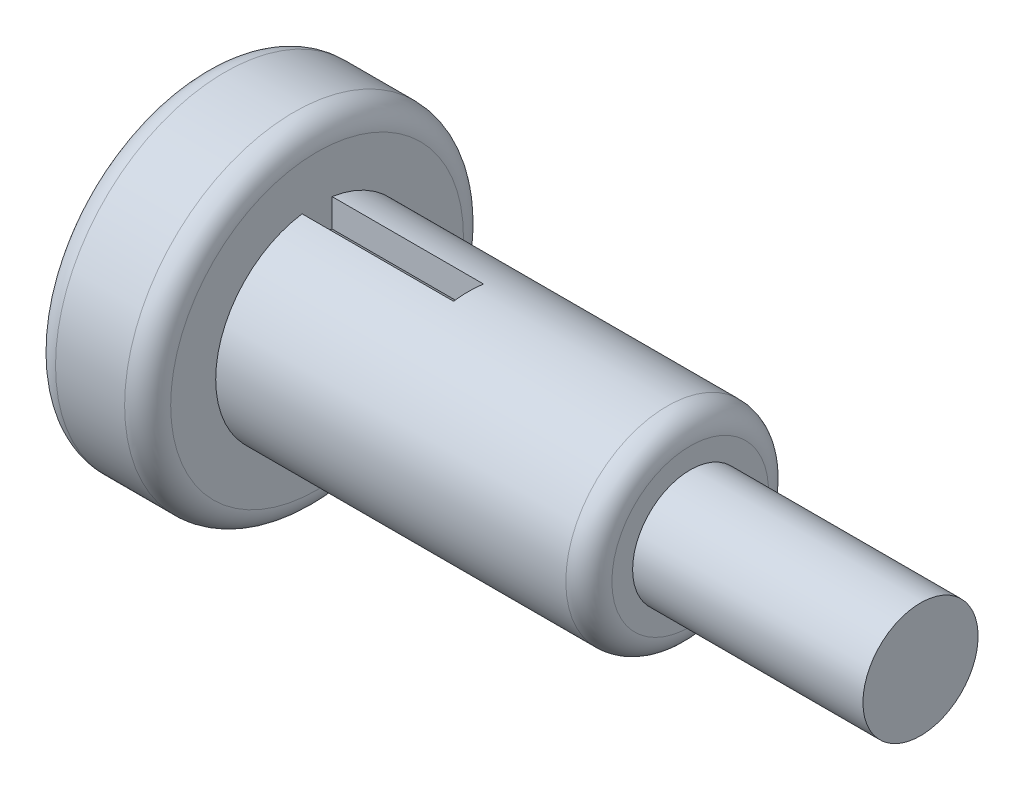
SolidWorks part; units mm, degrees
ref_plane "Front Plane" through (0, 0, 0) normal (0, 0, 1) x (1, 0, 0)
ref_plane "Top Plane" through (0, 0, 0) normal (0, 1, 0) x (1, 0, 0)
ref_plane "Right Plane" through (0, 0, 0) normal (1, 0, 0) x (0, 0, -1)
sketch "Sketch1" plane through (0, 0, 0) normal (0, 1, 0) x (1, 0, 0)
  line L0 (-25.6769, 0) -> (44.3231, 0)
  line L1 (44.3231, 0) -> (44.3231, 12.5)
  line L2 (44.3231, 12.5) -> (-5.6769, 12.5)
  line L3 (-5.6769, 12.5) -> (-5.6769, 17)
  line L4 (-10.6769, 22) -> (-86.6769, 22)
  line L5 (-86.6769, 22) -> (-86.6769, 31.7744)
  line L6 (-91.6769, 36.7744) -> (-106.6769, 36.7744)
  line L7 (-111.6769, 31.7744) -> (-111.6769, 21)
  line L8 (-106.6769, 16) -> (-25.6769, 16)
  line L9 (-25.6769, 16) -> (-25.6769, 0)
  arc A0 (-5.6769, 17) -> (-10.6769, 22) centre (-10.6769, 17) ccw
  arc A1 (-86.6769, 31.7744) -> (-91.6769, 36.7744) centre (-91.6769, 31.7744) ccw
  arc A2 (-106.6769, 16) -> (-111.6769, 21) centre (-106.6769, 21) cw
  arc A3 (-111.6769, 31.7744) -> (-106.6769, 36.7744) centre (-106.6769, 31.7744) cw
  point P14 (-5.6769, 22)
  point P17 (-86.6769, 36.7744)
  point P22 (-111.6769, 36.7744)
  dimension "D9" = 5
  dimension "D2" = 12.5
  dimension "D4" = 50
  dimension "D5" = 20
  dimension "D6" = 25
  dimension "D7" = 106
  dimension "D8" = 16
revolve "Revolve3" add sketch "Sketch1" angle 360 about L0
sketch "Sketch3" plane through (0, 0, 0) normal (0, 0, 1) x (1, 0, 0)
  line L0 (-86.6769, 0) -> (-86.6769, 50)
  line L1 (-86.6769, -22) -> (-86.6769, 22) construction
  line L2 (-86.6769, 0) -> (-86.6769, -56.4071)
  line L4 (-59.6769, -56.4071) -> (-51.6769, 50)
  line L6 (-86.6769, 50) -> (-51.6769, 50)
  line L7 (-86.6769, -56.4071) -> (-59.6769, -56.4071)
  dimension "D1" = 35
  dimension "D2" = 27
  dimension "D3" = 50
  dimension "D4" = 56.4071
extrude "Cut-Extrude1" cut sketch "Sketch3" against normal mid plane 6.5
